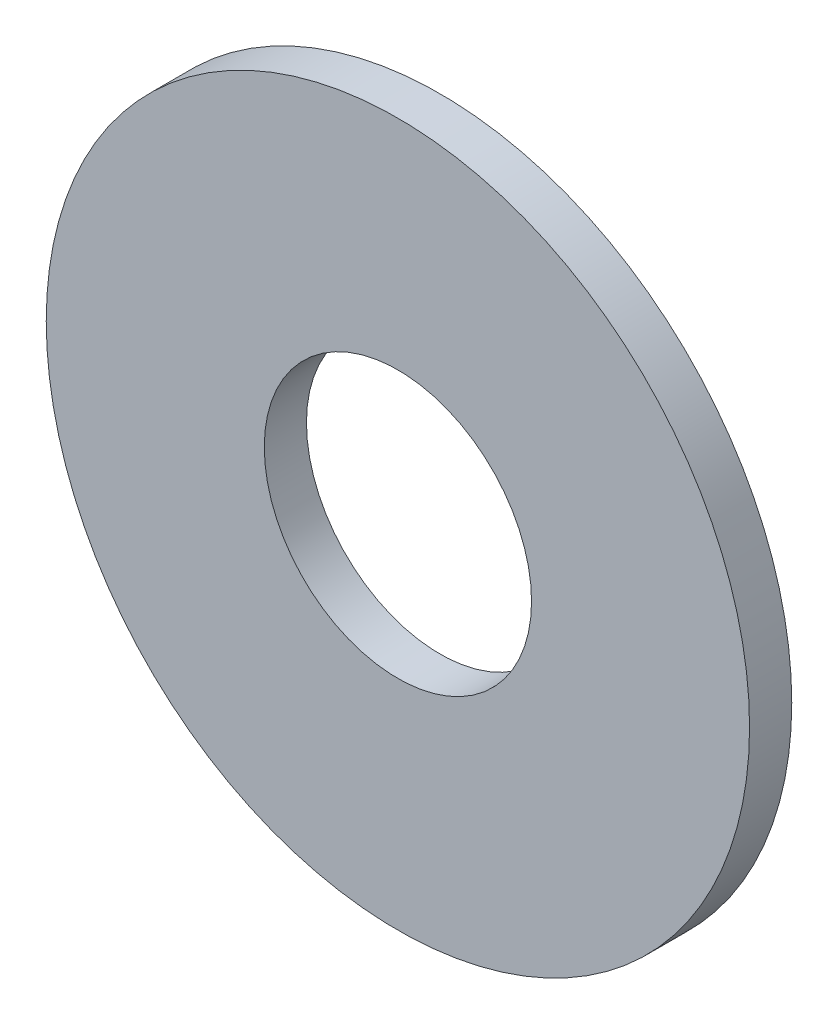
SolidWorks part; units mm, degrees
ref_plane "Front Plane" through (0, 0, 0) normal (0, 0, 1) x (1, 0, 0)
ref_plane "Top Plane" through (0, 0, 0) normal (0, 1, 0) x (1, 0, 0)
ref_plane "Right Plane" through (0, 0, 0) normal (1, 0, 0) x (0, 0, -1)
sketch "Sketch1" plane through (0, 0, 0) normal (0, 0, 1) x (1, 0, 0)
  circle A0 centre (0, 0) radius 9.5
  circle A1 centre (0, 0) radius 25
  dimension "D1" = 19
  dimension "D2" = 50
extrude "Boss-Extrude1" add sketch "Sketch1" along normal blind 3
